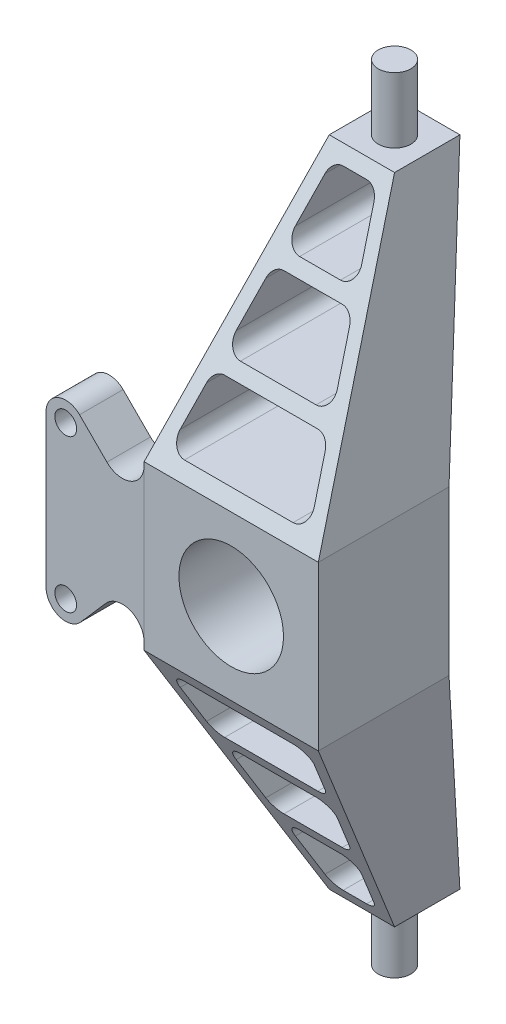
SolidWorks part; units mm, degrees
material "Cast Alloy Steel"
ref_plane "Front Plane" through (0, 0, 0) normal (0, 0, 1) x (1, 0, 0)
ref_plane "Top Plane" through (0, 0, 0) normal (0, 1, 0) x (1, 0, 0)
ref_plane "Right Plane" through (0, 0, 0) normal (1, 0, 0) x (0, 0, -1)
sketch "Sketch1" plane through (0, 0, 0) normal (1, 0, 0) x (0, 0, -1)
  line L1 (-15, -18.75) -> (-15, 18.75)
  line L2 (-15, 18.75) -> (15, 75)
  line L3 (15, 75) -> (30, 75)
  line L4 (30, 75) -> (15, 18.75)
  line L5 (15, 18.75) -> (15, -18.75)
  line L6 (-59.1587, 0) -> (-15, 0) construction
  line L7 (30, -75) -> (15, -18.75)
  line L8 (15, -75) -> (30, -75)
  line L9 (-15, -18.75) -> (15, -75)
  line L10 (15, 0) -> (64.9977, 0) construction
  line L11 (-15, 0) -> (0, 0) construction
  line L12 (0, 0) -> (15, 0) construction
  point P8 (15, 18.8912)
  dimension "D2" = 30
  dimension "D4" = 30
  dimension "D5" = 15
  dimension "D3" = 150
  dimension "D1" = 37.5
extrude "Boss-Extrude1" add sketch "Sketch1" along normal mid plane 40
sketch "Sketch2" plane through (0, 0, 15) normal (0, 0, 1) x (1, 0, 0)
  circle A0 centre (0, 0) radius 12
  dimension "D1" = 24
extrude "Cut-Extrude1" cut sketch "Sketch2" against normal through all both and the other way through all
sketch "Sketch3" plane through (0, 0, 15) normal (0, 0, 1) x (1, 0, 0)
  line L0 (-28.5355, 14.3995) -> (-34.818, 20.682)
  line L1 (-20, -18.75) -> (-20, 18.75) construction
  line L2 (-42.5, 17.5) -> (-42.5, -17.5)
  line L3 (-34.6124, -20.4621) -> (-28.764, -13.7737)
  line L4 (-20, -18.75) -> (-20, -17.065)
  line L5 (-20, 17.935) -> (-20, 18.75)
  arc A0 (-20, -17.065) -> (-28.764, -13.7737) centre (-25, -17.065) ccw
  arc A1 (-20, 17.935) -> (-28.5355, 14.3995) centre (-25, 17.935) cw
  arc A2 (-34.6124, -20.4621) -> (-42.5, -17.5) centre (-38, -17.5) cw
  arc A3 (-42.5, 17.5) -> (-34.818, 20.682) centre (-38, 17.5) cw
  circle A4 centre (-38, 17.5) radius 2.5
  circle A5 centre (-38, -17.5) radius 2.5
  arc A6 (-42.5, -17.5) -> (-34.6124, -20.4621) centre (-38, -17.5) ccw
  circle A7 centre (-38, -17.5) radius 4.5 construction
  point P8 (-20, -3.751)
  point P11 (-20, 5.864)
  point P18 (-42.5, 0)
  line M8 (-20, 18.75) -> (-20, -18.75)
  dimension "D1" = 5
  dimension "D2" = 2
  dimension "D4" = 5
  dimension "D3" = 35
  dimension "D5" = 18
  dimension "D6" = 45
extrude "Boss-Extrude2" add sketch "Sketch3" against normal blind 10 separate body contours A3 L2 A2 L3 A0 A1 L0 A5 A4 M8
sketch "Sketch5" plane through (0, 75, 0) normal (0, 1, 0) x (1, 0, 0)
  line L0 (0, 22.5) -> (0, 30) construction
  line L1 (20, 30) -> (-20, 30) construction
  line L2 (0, 22.5) -> (20, 22.5) construction
  line L3 (20, 15) -> (20, 30) construction
  circle A0 centre (0, 22.5) radius 3.75
  dimension "D1" = 7.5
extrude "Boss-Extrude3" add sketch "Sketch5" along normal blind 15
mirror "Mirror1" about plane through (0, 0, 0) normal (0, 1, 0) of "Boss-Extrude3"
sketch "Sketch6" plane through (0, 0, 15) normal (0, 0, 1) x (1, 0, 0)
  line L0 (-20, 18.75) -> (-7.5, 75)
  line L1 (20, 75) -> (-20, 75) construction
  line L2 (20, 18.75) -> (7.5, 75)
  line L4 (-20, 18.75) -> (-20, -18.75)
  line L5 (-20, -18.75) -> (20, -18.75)
  line L6 (20, -18.75) -> (20, 18.75)
  line L7 (20, 18.75) -> (-20, 18.75)
  line L10 (20, -18.75) -> (20, 18.75)
  line L12 (-7.5, 75) -> (-20, 75)
  line L16 (-20, 75) -> (-20, 18.75)
  line L17 (-20, 18.75) -> (20, 18.75)
  line L18 (20, 18.75) -> (20, 75)
  line L19 (20, 75) -> (-20, 75)
  line L20 (-20, 75) -> (-20, 18.75)
  line L22 (20, 18.75) -> (20, 75)
  line L23 (20, 75) -> (7.5, 75)
  dimension "D2" = 12.5
  dimension "D1" = 0
  dimension "D3" = 0
extrude "Cut-Extrude2" cut sketch "Sketch6" against normal through all both and the other way through all contours L22 L23 L2 | L20 L0 L12
mirror "Mirror2" about plane through (0, 0, 0) normal (0, 1, 0) of "Cut-Extrude2"
sketch "Sketch7" plane through (0, 0, 0) normal (0, 0, 1) x (1, 0, 0)
  line L0 (-12.4647, 22) -> (12.4647, 22)
  line L1 (15.3933, 25.6508) -> (13.6155, 33.6508)
  line L2 (2.687, 72) -> (-2.687, 72)
  line L3 (-5.6155, 69.6508) -> (-7.6155, 60.6508)
  line L4 (7.5, 75) -> (-7.5, 75) construction
  line L5 (-20, 18.75) -> (-7.5, 75) construction
  line L6 (20, 18.75) -> (7.5, 75) construction
  line L16 (-10.687, 36) -> (10.687, 36)
  line L17 (-8.687, 39) -> (8.687, 39)
  line L18 (-6.687, 54) -> (6.687, 54)
  line L19 (-4.687, 57) -> (4.687, 57)
  line L21 (-9.6155, 51.6508) -> (-11.6155, 42.6508)
  line L23 (7.6155, 60.6508) -> (5.6155, 69.6508)
  line L25 (-13.6155, 33.6508) -> (-15.3933, 25.6508)
  line L26 (11.6155, 42.6508) -> (9.6155, 51.6508)
  arc A0 (15.3933, 25.6508) -> (12.4647, 22) centre (12.4647, 25) cw
  arc A1 (13.6155, 33.6508) -> (10.687, 36) centre (10.687, 33) ccw
  arc A2 (-15.3933, 25.6508) -> (-12.4647, 22) centre (-12.4647, 25) ccw
  arc A3 (-13.6155, 33.6508) -> (-10.687, 36) centre (-10.687, 33) cw
  arc A4 (11.6155, 42.6508) -> (8.687, 39) centre (8.687, 42) cw
  arc A5 (-9.6155, 51.6508) -> (-6.687, 54) centre (-6.687, 51) cw
  arc A6 (9.6155, 51.6508) -> (6.687, 54) centre (6.687, 51) ccw
  arc A7 (-8.687, 39) -> (-11.6155, 42.6508) centre (-8.687, 42) cw
  arc A8 (7.6155, 60.6508) -> (4.687, 57) centre (4.687, 60) cw
  arc A9 (-7.6155, 60.6508) -> (-4.687, 57) centre (-4.687, 60) ccw
  arc A10 (5.6155, 69.6508) -> (2.687, 72) centre (2.687, 69) ccw
  arc A11 (-2.687, 72) -> (-5.6155, 69.6508) centre (-2.687, 69) ccw
  point P16 (0, 54)
  point P27 (-13.0935, 36)
  point P30 (12.4268, 39)
  point P33 (-9.0935, 54)
  point P38 (-12.4268, 39)
  point P41 (8.4268, 57)
  dimension "D7" = 3
  dimension "D3" = 3
  dimension "D4" = 3
  dimension "D5" = 14
  dimension "D6" = 15
  dimension "D8" = 3
  dimension "D2" = 15
  dimension "D1" = 3
  dimension "D9" = 3
extrude "Cut-Extrude3" cut sketch "Sketch7" against normal through all both and the other way through all
mirror "Mirror3" about plane through (0, 0, 0) normal (0, 1, 0) of "Cut-Extrude3"
equation "\"A\" = 30"
equation "\"B\" = 150"
equation "\"C\"= 15"
equation "\"D\"= \"B\" / 4"
equation "\"E\"= \"C\" / 2"
equation "\"D2@Sketch1\"=\"A\""
equation "\"D5@Sketch1\"=\"C\""
equation "\"D1@Sketch5\"=\"E\""
equation "\"D1@Boss-Extrude3\"=\"C\""
equation "\"D3@Sketch1\"=\"B\""
equation "\"D1@Sketch1\"=\"D\""
